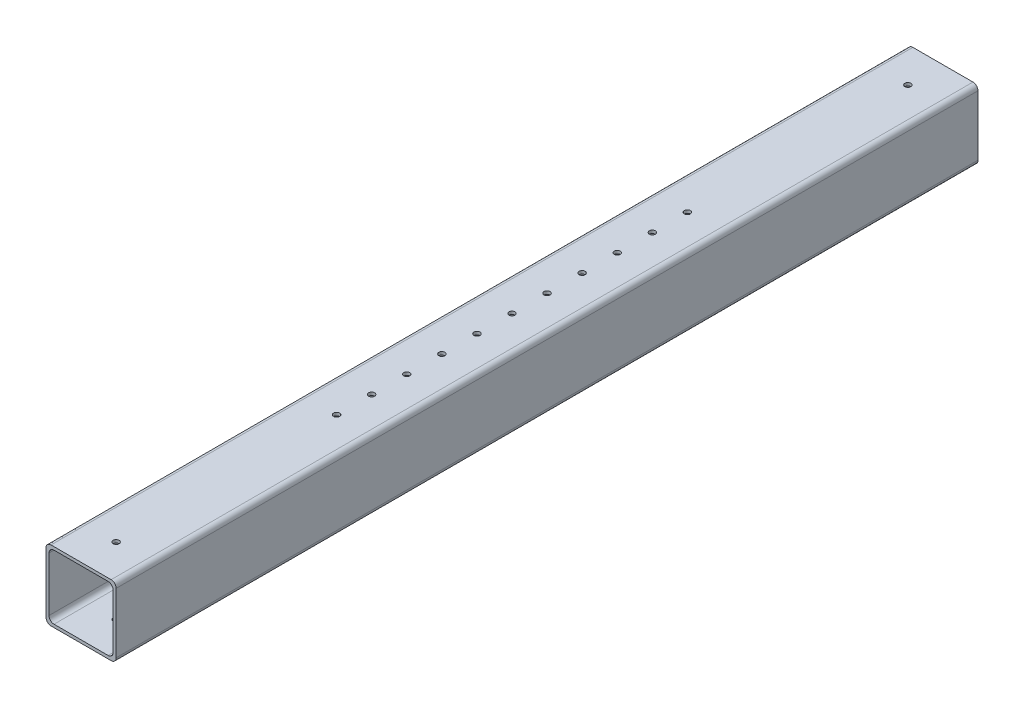
SolidWorks part; units mm, degrees
ref_plane "Front Plane" through (0, 0, 0) normal (0, 0, 1) x (1, 0, 0)
ref_plane "Top Plane" through (0, 0, 0) normal (0, 1, 0) x (1, 0, 0)
ref_plane "Right Plane" through (0, 0, 0) normal (1, 0, 0) x (0, 0, -1)
sketch "Sketch1" plane through (0, 0, 0) normal (0, 0, 1) x (1, 0, 0)
  line L0 (3, 67) -> (67, 67)
  line L1 (0, 0) -> (70, 0)
  line L2 (0, 0) -> (0, 70)
  line L3 (0, 70) -> (70, 70)
  line L4 (70, 0) -> (70, 70)
  line L5 (67, 3) -> (67, 67)
  line L6 (3, 3) -> (67, 3)
  line L7 (3, 3) -> (3, 67)
  dimension "D1" = 70
  dimension "D2" = 70
  dimension "D3" = 3
extrude "Boss-Extrude1" add sketch "Sketch1" along normal blind 860
fillet "Fillet1" radius 5 8 edges at (67, 67, 430) (0, 70, 430) (0, 0, 430) (67, 3, 430) (70, 0, 430) (3, 3, 430) (3, 67, 430) (70, 70, 430)
sketch "Sketch2" plane through (0, 70, 0) normal (0, 1, 0) x (1, 0, 0)
  line L0 (35, 0) -> (35, -860) construction
  line L1 (65, 0) -> (5, 0) construction
  line L2 (65, -860) -> (5, -860) construction
  circle A0 centre (35, -825) radius 3
  circle A1 centre (35, -35) radius 3
  dimension "D1" = 6
  dimension "D3" = 6
  dimension "D2" = 35
  dimension "D4" = 35
extrude "Cut-Extrude1" cut sketch "Sketch2" against normal blind 70
sketch "Sketch3" plane through (0, 0, 0) normal (0, -1, 0) x (1, 0, 0)
  line L0 (70, 860) -> (70, 0) construction
  line L1 (5, 860) -> (65, 860) construction
  circle A0 centre (35, 430) radius 3
  dimension "D2" = 6
  dimension "D1" = 35
  dimension "D3" = 430
extrude "Cut-Extrude2" cut sketch "Sketch3" against normal blind 173
pattern_linear "LPattern1" count 6 spacing 35 along (0, 0, -1) count 6 spacing 35 along (0, 0, 1) of "Cut-Extrude2"
